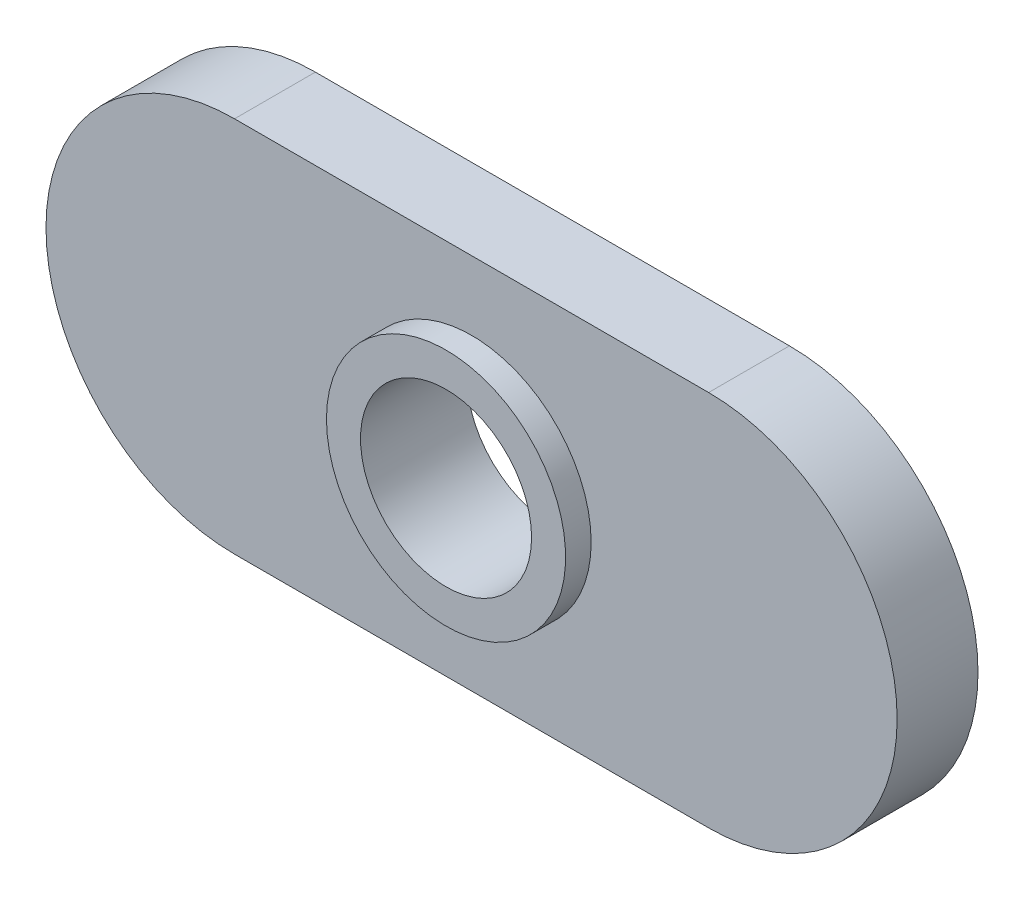
SolidWorks part; units mm, degrees
material "Zinc AC41A Alloy, As Cast"
ref_plane "Front Plane" through (0, 0, 0) normal (0, 0, 1) x (1, 0, 0)
ref_plane "Top Plane" through (0, 0, 0) normal (0, 1, 0) x (1, 0, 0)
ref_plane "Right Plane" through (0, 0, 0) normal (1, 0, 0) x (0, 0, -1)
ref_plane "Plane1" through (0, 0, 2.413) normal (0, 0, 1) x (1, 0, 0)
sketch "Sketch1" plane through (0, 0, 2.413) normal (0, 0, 1) x (1, 0, 0)
  line L0 (111.2787, 120.307) -> (125.4265, 120.307)
  line L1 (125.4265, 131.5592) -> (111.2787, 131.5592)
  arc A0 (111.2787, 131.5592) -> (111.2787, 120.307) centre (111.2787, 125.9331) ccw
  arc A1 (125.4265, 120.307) -> (125.4265, 131.5592) centre (125.4265, 125.9331) ccw
extrude "Boss-Extrude1" add sketch "Sketch1" against normal blind 2.413
ref_plane "Plane2" through (0, 125.9331, 0) normal (0, -1, 0) x (1, 0, 0)
sketch "Sketch2" plane through (0, 125.9331, 0) normal (0, -1, 0) x (1, 0, 0)
  line L0 (121.9213, 3.175) -> (118.3526, 3.175)
  line L1 (118.3526, 3.175) -> (118.3526, 2.413)
  line L2 (118.3526, 2.413) -> (121.9213, 2.413)
  line L3 (121.9213, 2.413) -> (121.9213, 3.175)
  line L4 (118.3526, 3.175) -> (118.3526, 2.413) construction
revolve "Revolve1" add sketch "Sketch2" angle 360 about L4
hole_wizard "1/4-20 Tapped Hole1" positions "Sketch6" profile "Sketch5" tap size "1/4-20" standard "Ansi Inch"
sketch "Sketch6" plane through (0, 0, 3.175) normal (0, 0, 1) x (1, 0, 0)
  point P6 (118.3526, 125.9331)
sketch "Sketch5" plane through (118.3526, 125.9331, 3.175) normal (1, 0, 0) x (0, -1, 0)
  line L0 (0, 0) -> (0, 18.0438)
  line L1 (0, 18.0438) -> (2.5527, 16.51)
  line L2 (2.5527, 16.51) -> (2.5527, 0)
  line L5 (2.5527, 0) -> (0, 0)
  line L10 (0, 18.0438) -> (-2.5527, 16.51) construction
  line L11 (0, -6.35) -> (0, 107.95) construction
  dimension "Tap Drill Dia." = 5.1054
  dimension "Tap Drill Depth" = 16.51
  dimension "Drill Angle" = 118
cosmetic thread "Hole Thread1"
